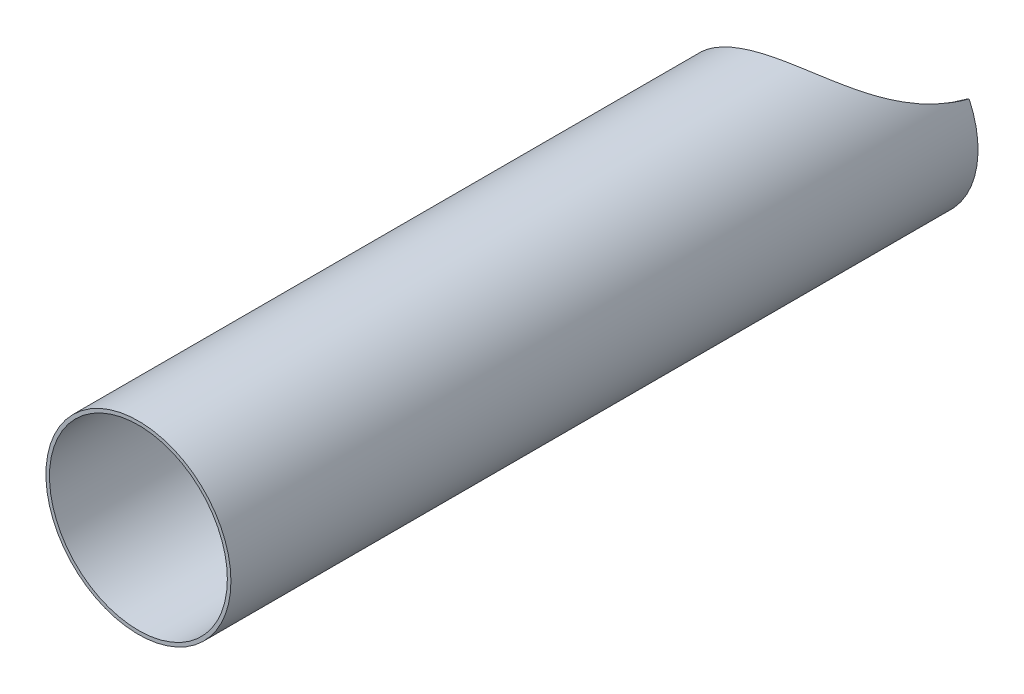
SolidWorks part; units mm, degrees
ref_plane "Plan de face" through (0, 0, 0) normal (0, 0, 1) x (1, 0, 0)
ref_plane "Plan de dessus" through (0, 0, 0) normal (0, 1, 0) x (1, 0, 0)
ref_plane "Plan de droite" through (0, 0, 0) normal (1, 0, 0) x (0, 0, -1)
sketch "Esquisse1" plane through (0, 0, 0) normal (0, 0, 1) x (1, 0, 0)
  circle A0 centre (0, 0) radius 26
  circle A1 centre (0, 0) radius 25
  dimension "D1" = 50
  dimension "D2" = 52
extrude "Boss.-Extru.1" add sketch "Esquisse1" along normal blind 210
sketch "Esquisse5" plane through (23.6249, 14.0733, 0) normal (-0.8591, -0.5118, 0) x (0, 0, 1)
  circle A0 centre (-10, 44.176) radius 47.6955
extrude "Enlèv. mat.-Extru.1" cut sketch "Esquisse5" along normal blind 60
